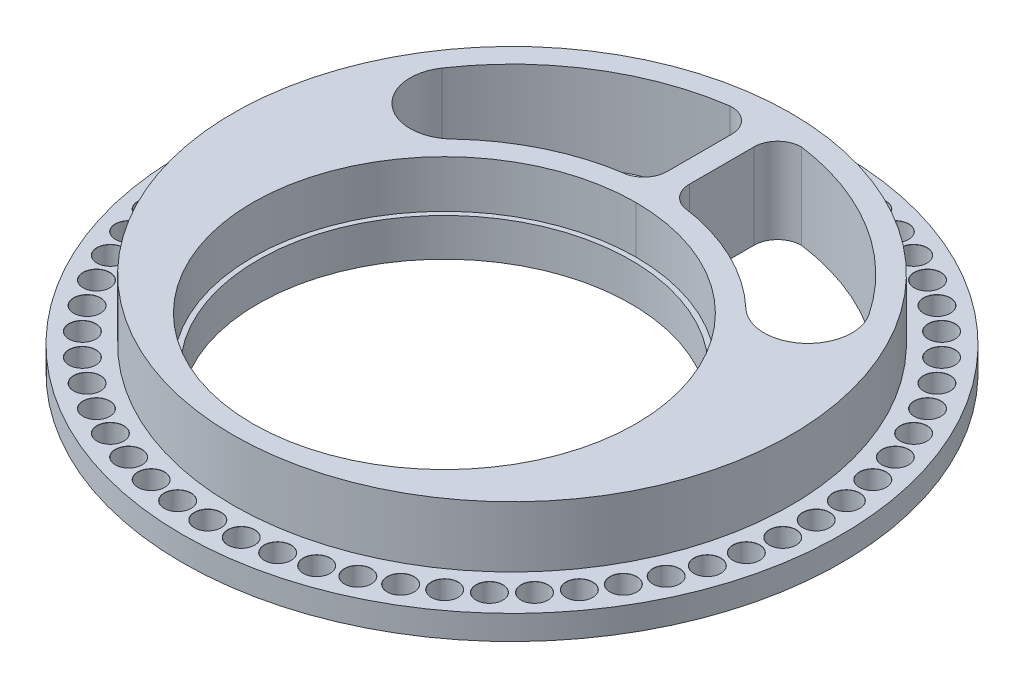
SolidWorks part; units mm, degrees
material "7075-T6, Plate (SS)"
ref_plane "X-Y Datum" through (0, 0, 0) normal (0, 0, 1) x (1, 0, 0)
ref_plane "X-Z Datum" through (0, 0, 0) normal (0, 1, 0) x (1, 0, 0)
ref_plane "Y-Z Datum" through (0, 0, 0) normal (1, 0, 0) x (0, 0, -1)
sketch "Sketch1" plane through (0, 0, 0) normal (0, 1, 0) x (1, 0, 0)
  line L0 (0, 0) -> (0, -12.7) construction
  line L1 (0, -43.0151) -> (0, 43.0151) construction
  line L2 (0, 61.9125) -> (0, 52.3875)
  circle A0 centre (0, -12.7) radius 35.052
  circle A1 centre (0, 0) radius 52.3875 construction
  circle A2 centre (0, 0) radius 57.15 construction
  circle A3 centre (0, 0) radius 61.9125
  point P12 (0, 57.15)
  dimension "D2" = 70.104
  dimension "D3" = 104.775
  dimension "D4" = 123.825
  dimension "D5" = 114.3
  dimension "D1" = 12.7
extrude "Boss-Extrude1" add sketch "Sketch1" along normal blind 4.5212 and the other way blind 0.0559
sketch "Sketch3" plane through (0, 4.5212, 0) normal (0, 1, 0) x (1, 0, 0)
  circle A0 centre (0, 0) radius 52.3875 construction
  circle A1 centre (0, 0) radius 52.3875
extrude "Boss-Extrude2" add sketch "Sketch3" along normal blind 11.43
sketch "Sketch4" plane through (0, -0.0559, 0) normal (0, -1, 0) x (1, 0, 0)
  circle A0 centre (0, 12.7) radius 35.052 construction
  circle A1 centre (0, 12.7) radius 35.052
extrude "Cut-Extrude1" cut sketch "Sketch4" against normal through all
sketch "Sketch9" plane through (0, 15.9512, 0) normal (0, 1, 0) x (1, 0, 0)
  circle A0 centre (0, -12.7) radius 35.052 construction
  circle A1 centre (0, -12.7) radius 35.052 construction
  circle A2 centre (0, -12.7) radius 36
  dimension "D1" = 72
extrude "Cut-Extrude3" cut sketch "Sketch9" against normal blind 8.89
hole_wizard "Ø5.0mm Dowel Hole1" positions "Sketch7" profile "Sketch8" hole size "Ø5.0" standard "ANSI Metric" end condition through all
sketch "Sketch7" plane through (0, 4.5212, 0) normal (0, 1, 0) x (1, 0, 0)
  point P0 (0, 57.15)
sketch "Sketch8" plane through (0, 4.5212, -57.15) normal (1, 0, 0) x (0, 0, 1)
  line L0 (0, 0) -> (0, 4.5771)
  line L1 (0, 4.5771) -> (2.5, 4.5771)
  line L2 (2.5, 4.5771) -> (2.5, 0.025)
  line L3 (2.5, 0.025) -> (2.525, 0)
  line L5 (2.525, 0) -> (0, 0)
  line L6 (-2.5, 0.025) -> (-2.525, 0) construction
  line L11 (0, -6.35) -> (0, 107.95) construction
  dimension "Thru Hole Dia." = 5
  dimension "Thru Hole Depth" = 4.5771
  dimension "Near C'Sink Dia." = 5.05
  dimension "Near C'Sink Angle" = 90
pattern_circular "CirPattern1" count 60 over 360 about axis through (0, 0, 0) along (0, 1, 0) of "Ø5.0mm Dowel Hole1"
ref_point "Point1"
ref_plane "Plane1" through (0, 0, 0) normal (1, 0, 0) x (0, 0, -1)
split line "Split Line1"
ref_plane "Plane2" through (0, 7.9477, 0) normal (0, 1, 0) x (1, 0, 0)
sketch "Sketch14" plane through (0, 7.9477, 0) normal (0, 1, 0) x (1, 0, 0)
  circle A0 centre (-33.2491, 22.3603) radius 8.255
ref_point "Point4"
sketch "Sketch10" plane through (0, 15.9512, 0) normal (0, 1, 0) x (1, 0, 0)
  circle A0 centre (0, 0) radius 52.3875 construction
  circle A1 centre (0, 0) radius 52.3875 construction
  circle A3 centre (-33.2491, 22.3603) radius 8.255 construction
  circle A4 centre (33.2491, 22.3603) radius 8.255 construction
  arc A7 (0, -52.764) -> (0, 27.364) centre (0, -12.7) ccw
  arc A8 (0, 27.364) -> (0, -52.764) centre (0, -12.7) ccw
  arc A9 (0, -52.764) -> (0, 27.364) centre (0, -12.7) ccw construction
  arc A10 (0, 27.364) -> (0, -52.764) centre (0, -12.7) ccw construction
  circle A29 centre (0, 0) radius 48.3235 construction
  arc A30 (-27.5687, 16.3704) -> (27.5687, 16.3704) centre (0, -12.7) cw
  arc A31 (-40.0992, 26.967) -> (40.0992, 26.967) centre (0, 0) cw
  arc A32 (-40.0992, 26.967) -> (-27.5687, 16.3704) centre (-33.2491, 22.3603) ccw
  arc A33 (27.5687, 16.3704) -> (40.0992, 26.967) centre (33.2491, 22.3603) ccw
  dimension "D3" = 16.51
  dimension "D1" = 4.064
  dimension "D2" = 4.064
extrude "Cut-Extrude5" cut sketch "Sketch10" against normal through all contours A33 A31 A32 A30
sketch "Sketch15" plane through (0, 7.9477, 0) normal (0, 1, 0) x (1, 0, 0)
  line L1 (-2.1171, 31.2835) -> (-2.1171, 43.3958)
  line L4 (2.032, 31.291) -> (2.032, 43.4389)
  line L6 (-2.1764, 48.3235) -> (-2.1667, 48.2749) construction
  line L8 (2.1667, 48.2749) -> (2.1764, 48.3235) construction
  arc A0 (27.5687, 16.3704) -> (-27.5687, 16.3704) centre (0, -12.7) ccw construction
  arc A1 (27.5687, 16.3704) -> (-27.5687, 16.3704) centre (0, -12.7) ccw construction
  arc A2 (40.0992, 26.967) -> (-40.0992, 26.967) centre (0, 0) ccw construction
  arc A3 (-2.1171, 43.3958) -> (-6.9062, 47.8275) centre (-6.5621, 43.3958) ccw
  arc A4 (40.0992, 26.967) -> (-40.0992, 26.967) centre (0, 0) ccw construction
  arc A5 (6.5037, 47.8838) -> (2.032, 43.4389) centre (6.477, 43.4389) ccw
  arc A7 (-2.1171, 31.2835) -> (-5.362, 27.0036) centre (-6.5621, 31.2835) cw
  arc A9 (2.032, 31.291) -> (5.2509, 27.0184) centre (6.477, 31.291) ccw
  arc A10 (-6.9062, 47.8275) -> (6.5037, 47.8838) centre (0, 0) cw
  arc A11 (-5.362, 27.0036) -> (5.2509, 27.0184) centre (0, -12.7) cw
  point P9 (0, 37.4715)
  dimension "D1" = 4.445
  dimension "D2" = 2.1171
  dimension "D3" = 4.445
  dimension "D4" = 2.032
  dimension "D5" = 43.4389
  dimension "D6" = 31.2835
  dimension "D7" = 2.1171
  dimension "D8" = 12.148
  dimension "D9" = 12.1123
extrude "Boss-Extrude3" add sketch "Sketch15" along normal up to surface and the other way up to surface contours A9 L4 A5 A10 A3 L1 A7 A11 up to face at (0, 15.9512, -26.9504) other way up to face at (0, -0.0559, -26.9504)
sketch "Sketch16" plane through (0, 0, 0) normal (1, 0, 0) x (0, 0, -1)
  line L0 (0, 0) -> (0, 15.9512)
  line L1 (52.3875, 15.9512) -> (-52.3875, 15.9512) construction
  dimension "D1" = 15.9512
sketch "Sketch18" plane through (0, 7.0612, 0) normal (0, 1, 0) x (1, 0, 0)
  line L0 (0, 23.3) -> (0, 22.352)
  circle A0 centre (0, -12.7) radius 35.052 construction
  dimension "D1" = 0.948
